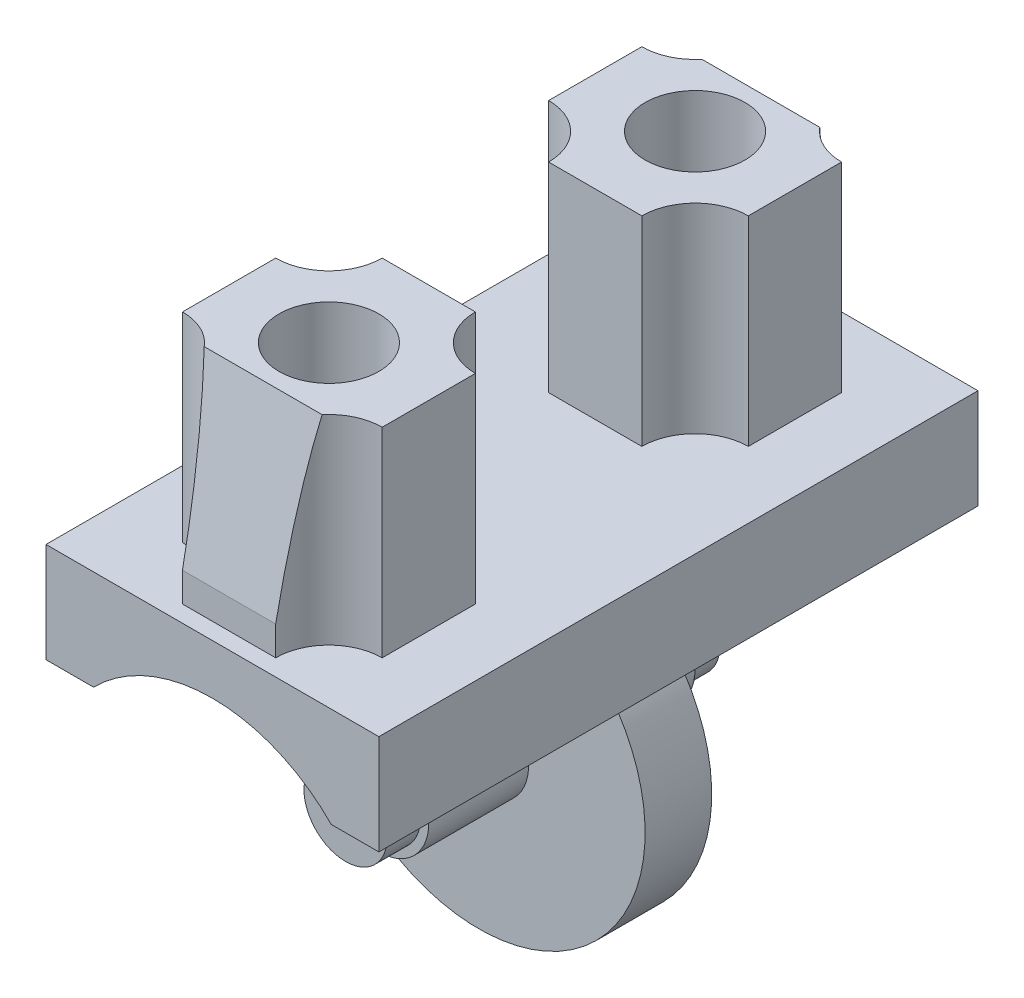
SolidWorks part; units mm, degrees
material "ABS"
ref_plane "Front Plane" through (0, 0, 0) normal (0, 0, 1) x (1, 0, 0)
ref_plane "Top Plane" through (0, 0, 0) normal (0, 1, 0) x (1, 0, 0)
ref_plane "Right Plane" through (0, 0, 0) normal (1, 0, 0) x (0, 0, -1)
sketch "Sketch1" plane through (0, 0, 0) normal (0, 0, 1) x (1, 0, 0)
  line L1 (0, 0) -> (7.9375, 0)
  line L2 (0, 0) -> (0, -2.3813)
  line L3 (0, -2.3813) -> (7.9375, -2.3813)
  line L4 (7.9375, 0) -> (7.9375, -2.3813)
  dimension "D1" = 7.9375
  dimension "D2" = 2.3813
extrude "Boss-Extrude1" add sketch "Sketch1" along normal blind 7.1437
sketch "Sketch2" plane through (0, 0, 0) normal (0, 0, -1) x (-1, 0, 0)
  line L0 (-7.9375, 0) -> (0, 0) construction
  line L1 (-3.9688, -5.1594) -> (-3.9688, 0) construction
  circle A0 centre (-3.9688, -5.1594) radius 3.9688
  dimension "D2" = 7.9375
  dimension "D1" = 5.1594
extrude "Boss-Extrude2" add sketch "Sketch2" against normal blind 0.7937
sketch "Sketch3" plane through (0, 0, 0.7937) normal (0, 0, 1) x (1, 0, 0)
  circle A0 centre (3.9688, -5.1594) radius 3.9688
  arc A1 (1.1345, -2.3813) -> (6.803, -2.3813) centre (3.9688, -5.1594) ccw construction
extrude "Cut-Extrude1" cut sketch "Sketch3" along normal through all
sketch "Sketch4" plane through (0, 0, 0) normal (0, 1, 0) x (1, 0, 0)
  line L0 (0, 0) -> (0, -7.1437) construction
  line L1 (1.5875, -1.9844) -> (6.35, -1.9844)
  line L2 (1.5875, -1.9844) -> (1.5875, -6.7469)
  line L3 (1.5875, -6.7469) -> (6.35, -6.7469)
  line L4 (6.35, -1.9844) -> (6.35, -6.7469)
  line L5 (0, -3.5719) -> (7.9375, -3.5719) construction
  line L6 (7.9375, -7.1437) -> (7.9375, 0) construction
  line L7 (1.5875, -4.3656) -> (6.35, -4.3656) construction
  line L8 (3.9688, -1.9844) -> (3.9688, -6.7469) construction
  line L9 (7.9375, 0) -> (0, 0) construction
  line L10 (3.9688, 0) -> (3.9688, -7.1437) construction
  line L11 (7.9375, -7.1437) -> (0, -7.1437) construction
  point P20 (3.9688, -4.3656)
  dimension "D1" = 4.7625
  dimension "D2" = 90
  dimension "D3" = 0.3969
extrude "Boss-Extrude3" add sketch "Sketch4" along normal blind 4.7625
sketch "Sketch5" plane through (0, 4.7625, 0) normal (0, 1, 0) x (1, 0, 0)
  line L0 (3.9688, -1.9844) -> (3.9688, -6.7469) construction
  line L1 (6.35, -1.9844) -> (1.5875, -1.9844) construction
  line L2 (1.5875, -6.7469) -> (6.35, -6.7469) construction
  line L3 (6.35, -4.3656) -> (1.5875, -4.3656) construction
  line L4 (6.35, -6.7469) -> (6.35, -1.9844) construction
  line L5 (1.5875, -1.9844) -> (1.5875, -6.7469) construction
  line L6 (1.5875, -1.9844) -> (1.5875, -6.7469) construction
  circle A0 centre (1.5875, -6.7469) radius 1.27
  circle A1 centre (1.5875, -1.9844) radius 1.27
  circle A2 centre (6.35, -1.9844) radius 1.27
  circle A3 centre (6.35, -6.7469) radius 1.27
  circle A4 centre (3.9688, -4.3656) radius 1.1906
  dimension "D1" = 2.54
  dimension "D2" = 2.3813
extrude "Cut-Extrude2" cut sketch "Sketch5" against normal blind 4.7625
sketch "Sketch6" plane through (1.5875, 0, 0) normal (-1, 0, 0) x (0, 0, 1)
  line L0 (6.7469, 0) -> (6.7469, 0.6985) construction
  line L1 (6.7469, 4.7625) -> (6.7469, 0) construction
  line L2 (6.7469, 0.6985) -> (6.7469, 5.7785)
  line L3 (6.7469, 5.7785) -> (5.7309, 5.7785)
  line L4 (5.7309, 5.7785) -> (6.7469, 0.6985)
  dimension "D1" = 0.6985
  dimension "D2" = 5.08
  dimension "D3" = 1.016
extrude "Cut-Extrude3" cut sketch "Sketch6" against normal through all
sketch "Sketch7" plane through (0, 0, 0.7937) normal (0, 0, 1) x (1, 0, 0)
  circle A0 centre (3.9688, -5.1594) radius 1.1906
  dimension "D1" = 2.3813
extrude "Boss-Extrude4" add sketch "Sketch7" along normal blind 2.3813
sketch "Sketch8" plane through (0, 0, 3.175) normal (0, 0, 1) x (1, 0, 0)
  circle A0 centre (3.9688, -5.1594) radius 0.9922
  dimension "D1" = 1.9844
extrude "Boss-Extrude5" add sketch "Sketch8" along normal blind 0.7937
sketch "Sketch9" plane through (0, 0, 3.9688) normal (0, 0, 1) x (1, 0, 0)
  line L0 (3.9688, -3.9688) -> (3.9688, -5.1594) construction
  line L1 (2.9527, -3.9688) -> (4.9848, -3.9688)
  line L2 (2.9527, -3.9688) -> (2.9527, -4.7625)
  line L3 (2.9527, -4.7625) -> (4.9848, -4.7625)
  line L4 (4.9848, -3.9688) -> (4.9848, -4.7625)
  circle A0 centre (3.9688, -5.1594) radius 1.1906 construction
  circle A2 centre (3.9688, -5.1594) radius 1.1906 construction
  point P6 (3.9688, -3.9688)
  dimension "D1" = 0.7937
  dimension "D2" = 2.032
extrude "Cut-Extrude4" cut sketch "Sketch9" against normal blind 0.7937
mirror "Mirror1" about plane through (0, 0, 0) normal (0, 0, 1) of "Cut-Extrude4", "Boss-Extrude5", "Boss-Extrude4", "Cut-Extrude3", "Cut-Extrude2", "Boss-Extrude3", "Cut-Extrude1", "Boss-Extrude2", "Boss-Extrude1"
